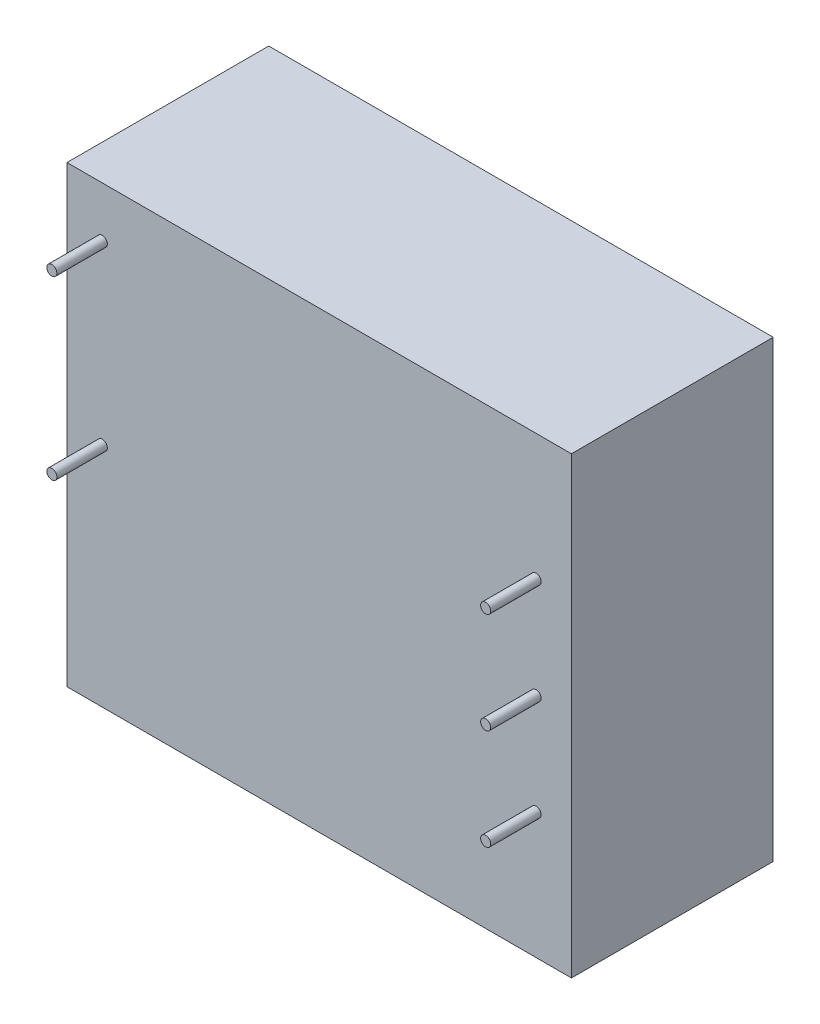
SolidWorks part; units mm, degrees
ref_plane "Спереди" through (0, 0, 0) normal (0, 0, 1) x (1, 0, 0)
ref_plane "Сверху" through (0, 0, 0) normal (0, 1, 0) x (1, 0, 0)
ref_plane "Справа" through (0, 0, 0) normal (1, 0, 0) x (0, 0, -1)
sketch "Эскиз1" plane through (0, 0, 0) normal (0, 0, 1) x (1, 0, 0)
  line L0 (-12.7766, 0) -> (34.3985, 0) construction
  line L1 (-25, -22.5) -> (25, -22.5)
  line L2 (-25, -22.5) -> (-25, 22.5)
  line L3 (-25, 22.5) -> (25, 22.5)
  line L4 (25, -22.5) -> (25, 22.5)
  line L5 (0, 20.0775) -> (0, -20.0775) construction
  dimension "D1" = 50
  dimension "D2" = 45
extrude "Вытянуть1" add sketch "Эскиз1" along normal blind 20
sketch "Эскиз2" plane through (0, 0, 20) normal (0, 0, 1) x (1, 0, 0)
  line L0 (-18.0461, 0) -> (14.4044, 0) construction
  line L1 (0, 17.3308) -> (0, -10.3725) construction
  line L2 (-21.5, 17.5) -> (-21.5, -9.277) construction
  line L3 (21.5, 19.997) -> (21.5, -12.1933) construction
  line L4 (25, -22.5) -> (25, 22.5) construction
  circle A0 centre (-21.5, 17.5) radius 0.5
  circle A1 centre (-21.5, 0) radius 0.5
  circle A2 centre (21.5, 0) radius 0.5
  circle A3 centre (21.5, 10) radius 0.5
  circle A4 centre (21.5, -10) radius 0.5
  dimension "D3" = 17.5
  dimension "D4" = 10
  dimension "D5" = 1
  dimension "D1" = 21.5
  dimension "D2" = 3.5
extrude "Вытянуть2" add sketch "Эскиз2" along normal blind 5
